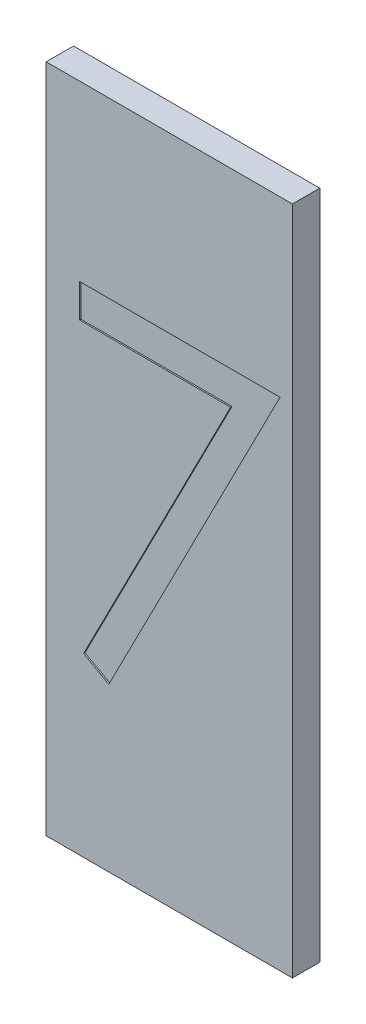
SolidWorks part; units mm, degrees
ref_plane "正面" through (0, 0, 0) normal (0, 0, 1) x (1, 0, 0)
ref_plane "平面" through (0, 0, 0) normal (0, 1, 0) x (1, 0, 0)
ref_plane "右側面" through (0, 0, 0) normal (1, 0, 0) x (0, 0, -1)
sketch "ｽｹｯﾁ1" plane through (0, 0, 0) normal (0, 0, 1) x (1, 0, 0)
  line L0 (18, 0) -> (0, 0)
  line L1 (18, 49) -> (0, 49)
  line L2 (0, 0) -> (0, 49)
  line L4 (18, 0) -> (18, 49)
extrude "ﾎﾞｽ - 押し出し1" add sketch "ｽｹｯﾁ1" along normal blind 2
sketch "ｽｹｯﾁ2" plane through (0, 0, 2) normal (0, 0, 1) x (1, 0, 0)
  text T0 "7" font "Century Gothic" height in points 90
extrude "ｶｯﾄ - 押し出し1" cut sketch "ｽｹｯﾁ2" against normal blind 0.1
